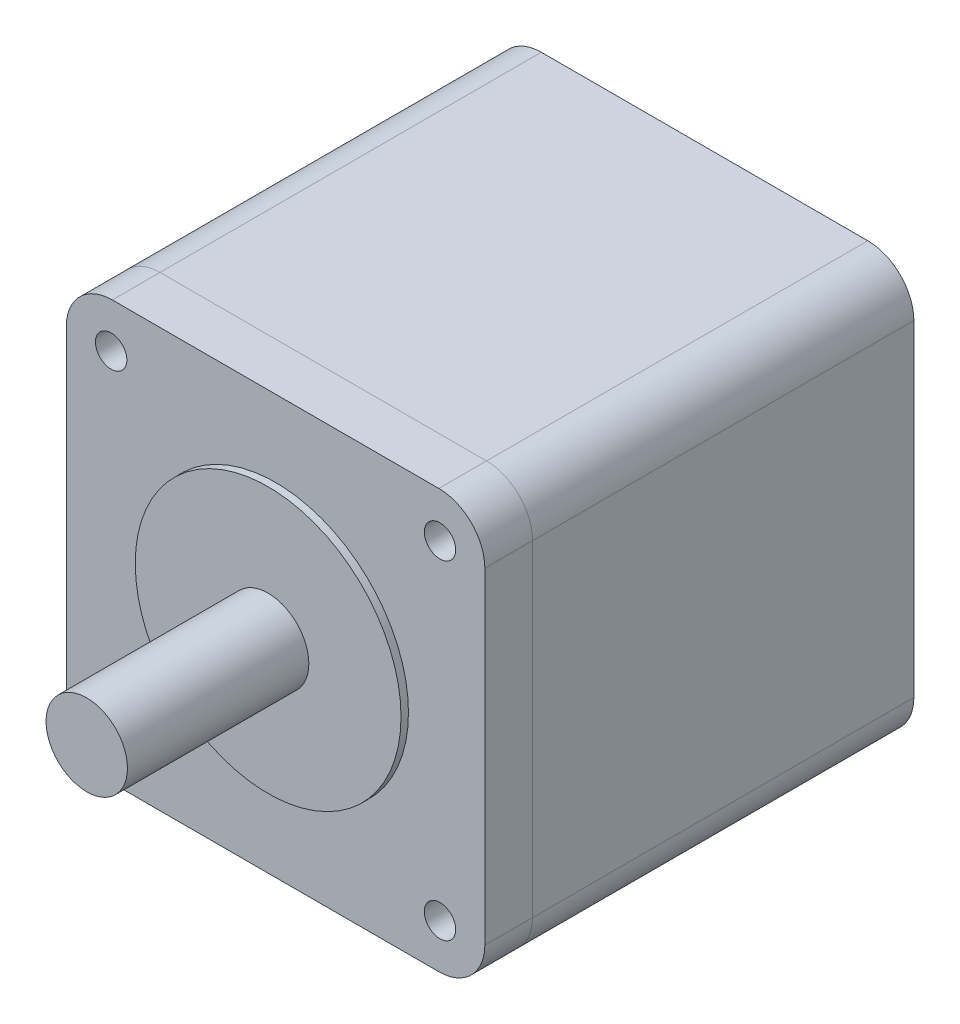
SolidWorks part; units mm, degrees
ref_plane "前视基准面" through (0, 0, 0) normal (0, 0, 1) x (1, 0, 0)
ref_plane "上视基准面" through (0, 0, 0) normal (0, 1, 0) x (1, 0, 0)
ref_plane "右视基准面" through (0, 0, 0) normal (1, 0, 0) x (0, 0, -1)
other "Configuration Table"
sketch "草图1" plane through (0, 0, 0) normal (0, 0, 1) x (1, 0, 0)
  line L1 (-70.206, -90) -> (70.206, -90)
  line L2 (-90, -70.206) -> (-90, 70.206)
  line L3 (-70.206, 90) -> (70.206, 90)
  line L4 (90, -70.206) -> (90, 70.206)
  line L5 (-90, -90) -> (90, 90) construction
  line L6 (-90, 90) -> (90, -90) construction
  arc A0 (-70.206, -90) -> (-90, -70.206) centre (-70.206, -70.206) cw
  arc A1 (70.206, -90) -> (90, -70.206) centre (70.206, -70.206) ccw
  arc A2 (90, 70.206) -> (70.206, 90) centre (70.206, 70.206) ccw
  arc A3 (-70.206, 90) -> (-90, 70.206) centre (-70.206, 70.206) ccw
  point P0 (0, 0)
  dimension "D3" = 19.794
  dimension "D1" = 180
  dimension "D2" = 180
extrude "凸台-拉伸1" add sketch "草图1" along normal blind 20.5
sketch "草图2" plane through (0, 0, 20.5) normal (0, 0, 1) x (1, 0, 0)
  line L0 (0, 0) -> (0, 37.4836) construction
  line L1 (0, 0) -> (-37.4238, 0) construction
  circle A0 centre (0, 0) radius 100 construction
  circle A1 centre (-70.7107, 70.7107) radius 6.75
  circle A2 centre (70.7107, 70.7107) radius 6.75
  circle A3 centre (70.7107, -70.7107) radius 6.75
  circle A4 centre (-70.7107, -70.7107) radius 6.75
  point P18 (0, 0)
  dimension "D1" = 70.7107
  dimension "D3" = 4
  dimension "D2" = 70.7107
extrude "切除-拉伸1" cut sketch "草图2" against normal up to next
sketch "草图3" plane through (0, 0, 0) normal (0, 0, -1) x (-1, 0, 0)
  line L1 (-70.206, -90) -> (70.206, -90)
  line L2 (-90, -70.206) -> (-90, 70.206)
  line L3 (-70.206, 90) -> (70.206, 90)
  line L4 (90, -70.206) -> (90, 70.206)
  line L5 (-90, -90) -> (90, 90) construction
  line L6 (-90, 90) -> (90, -90) construction
  arc A0 (-70.206, -90) -> (-90, -70.206) centre (-70.206, -70.206) cw
  arc A1 (70.206, -90) -> (90, -70.206) centre (70.206, -70.206) ccw
  arc A2 (90, 70.206) -> (70.206, 90) centre (70.206, 70.206) ccw
  arc A3 (-70.206, 90) -> (-90, 70.206) centre (-70.206, 70.206) ccw
  point P0 (0, 0)
  dimension "D1" = 19.794
extrude "凸台-拉伸2" add sketch "草图3" along normal blind 164 separate body
sketch "草图4" plane through (0, 0, 20.5) normal (0, 0, 1) x (1, 0, 0)
  circle A0 centre (0, 0) radius 57.15
  dimension "D1" = 114.3
extrude "凸台-拉伸3" add sketch "草图4" along normal blind 3.2
sketch "草图5" plane through (0, 0, 23.7) normal (0, 0, 1) x (1, 0, 0)
  circle A0 centre (0, 0) radius 17.5
extrude "凸台-拉伸4" add sketch "草图5" along normal blind 78
sketch "草图6" [suppressed] plane through (0, 0, 99.5) normal (0, 0, 1) x (1, 0, 0)
  line L0 (-32.3373, 0) -> (34.2921, 0) construction
  line L1 (0, 33.9405) -> (0, -23.7051) construction
  line L3 (12.5, 5) -> (20.5, 5)
  line L4 (12.5, 5) -> (12.5, -5)
  line L5 (12.5, -5) -> (20.5, -5)
  line L6 (20.5, 5) -> (20.5, -5)
  dimension "D1" = 10
  dimension "D2" = 8
  dimension "D3" = 5
  dimension "D4" = 12.5
extrude "凸台-拉伸5" [suppressed] add sketch "草图6" against normal blind 55
sketch "草图8" [suppressed] plane through (20.5, 0, 0) normal (1, 0, 0) x (0, 0, -1)
  line L0 (-44.5, -5) -> (-44.5, 5) construction
  line L1 (-44.5, 5) -> (-99.5, 5) construction
  line L2 (-44.5, 5) -> (-44.5, -5)
  arc A0 (-44.5, 5) -> (-44.5, -5) centre (-44.5, 0) cw
extrude "凸台-拉伸6" [suppressed] add sketch "草图8" against normal up to next
